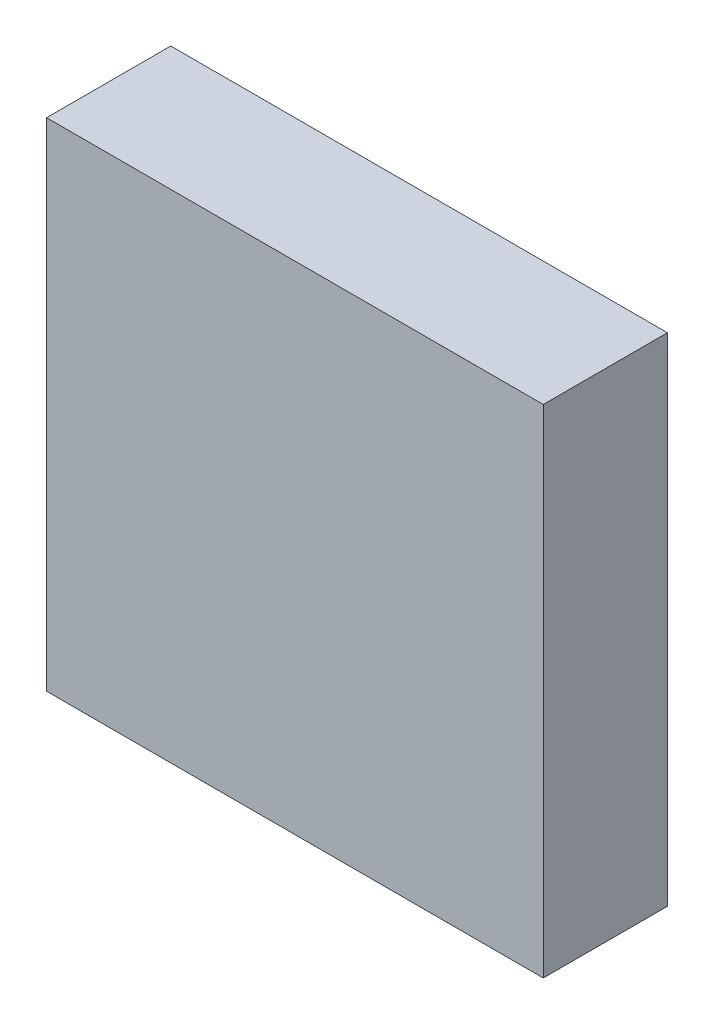
SolidWorks part; units mm, degrees
ref_plane "前视基准面" through (0, 0, 0) normal (0, 0, 1) x (1, 0, 0)
ref_plane "上视基准面" through (0, 0, 0) normal (0, 1, 0) x (1, 0, 0)
ref_plane "右视基准面" through (0, 0, 0) normal (1, 0, 0) x (0, 0, -1)
other "Configuration Table"
sketch "草图1" plane through (0, 0, 0) normal (0, 0, 1) x (1, 0, 0)
  line L1 (-20000, -20000) -> (20000, -20000)
  line L2 (-20000, -20000) -> (-20000, 20000)
  line L3 (-20000, 20000) -> (20000, 20000)
  line L4 (20000, -20000) -> (20000, 20000)
extrude "凸台-拉伸1" add sketch "草图1" against normal blind 10000
